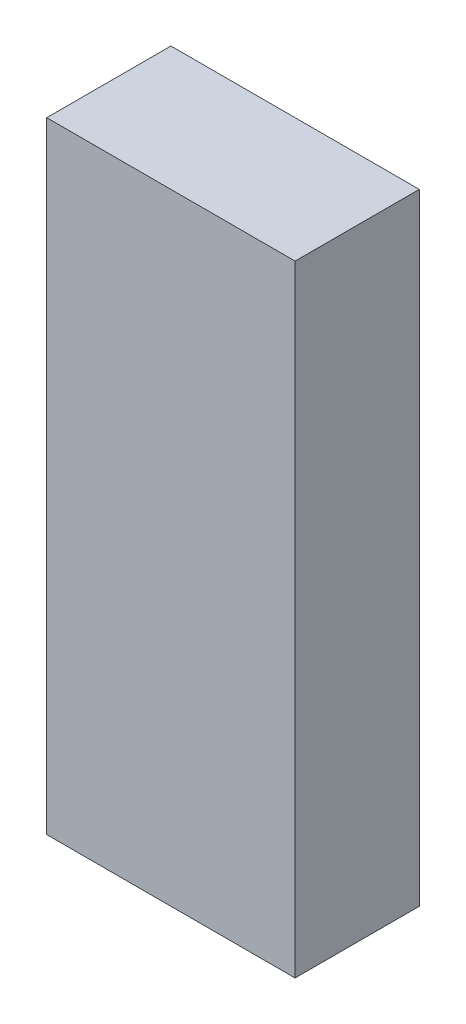
SolidWorks part; units mm, degrees
ref_plane "Front Plane" through (0, 0, 0) normal (0, 0, 1) x (1, 0, 0)
ref_plane "Top Plane" through (0, 0, 0) normal (0, 1, 0) x (1, 0, 0)
ref_plane "Right Plane" through (0, 0, 0) normal (1, 0, 0) x (0, 0, -1)
sketch "Sketch1" plane through (0, 0, 0) normal (0, 0, 1) x (1, 0, 0)
  line L1 (10, -25) -> (-10, -25)
  line L2 (10, -25) -> (10, 25)
  line L3 (10, 25) -> (-10, 25)
  line L4 (-10, -25) -> (-10, 25)
  line L5 (10, -25) -> (-10, 25) construction
  line L6 (10, 25) -> (-10, -25) construction
  point P0 (0, 0)
  dimension "D1" = 20
  dimension "D2" = 50
extrude "Boss-Extrude1" add sketch "Sketch1" along normal blind 10
